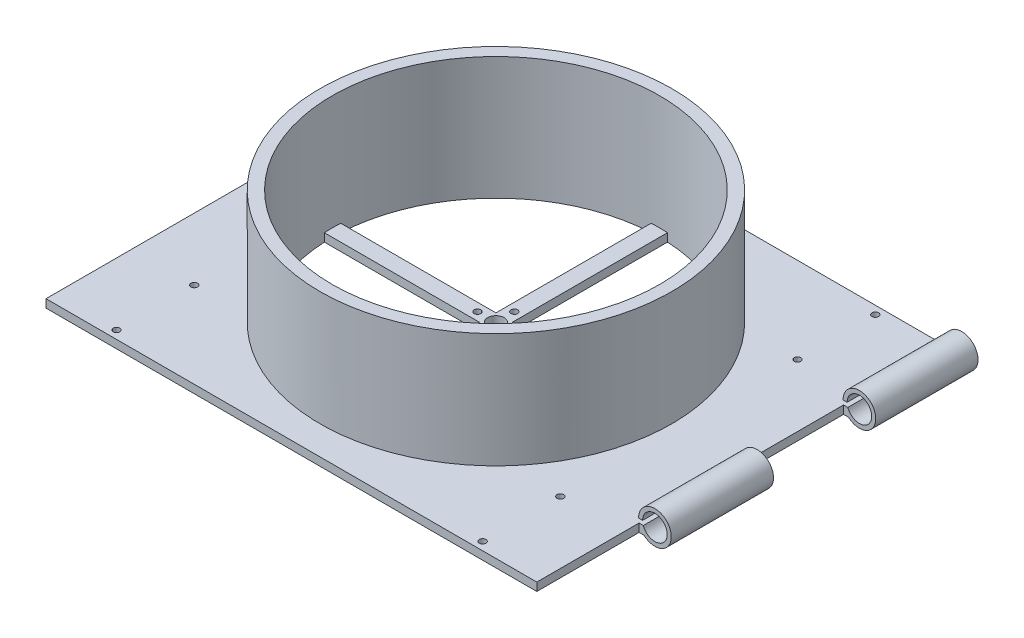
SolidWorks part; units mm, degrees
ref_plane "Alzado" through (0, 0, 0) normal (0, 0, 1) x (1, 0, 0)
ref_plane "Planta" through (0, 0, 0) normal (0, 1, 0) x (1, 0, 0)
ref_plane "Vista lateral" through (0, 0, 0) normal (1, 0, 0) x (0, 0, -1)
sketch "Croquis1" plane through (0, 0, 0) normal (0, 1, 0) x (1, 0, 0)
  circle A0 centre (0, 0) radius 40
  circle A1 centre (0, 0) radius 43
  point P7 (0, 0)
  point P10 (0, 0)
  dimension "D1" = 80
  dimension "D2" = 3
extrude "Saliente-Extruir1" add sketch "Croquis1" along normal blind 30 contours A1 A0
sketch "Croquis3" plane through (0, 0, 0) normal (0, 1, 0) x (1, 0, 0)
  line L1 (0, -40) -> (0, 40) construction
  line L8 (-40, 0) -> (40, 0) construction
  line L13 (-2, 2) -> (-2, 39.95)
  line L18 (-2, -39.95) -> (-2, -2)
  line L20 (2, -39.95) -> (2, -2)
  line L22 (-1.9287, -39.9535) -> (1.9287, 39.9535) construction
  line L23 (-1.9287, 39.9535) -> (1.9287, -39.9535) construction
  line L24 (-39.95, -2) -> (-2, -2)
  line L27 (-39.95, 2) -> (-2, 2)
  line L29 (-39.9548, -1.9002) -> (39.9548, 1.9002) construction
  line L30 (-39.9548, 1.9002) -> (39.9548, -1.9002) construction
  line L31 (2, 2) -> (39.95, 2)
  line L32 (2, 2) -> (2, 39.95)
  line L33 (2, -2) -> (39.95, -2)
  circle A0 centre (0, 0) radius 40 construction
  circle A1 centre (0, 0) radius 40
  circle A2 centre (0, 0) radius 2
  circle A3 centre (4.5, 0) radius 0.81
  circle A9 centre (-4.5, 0) radius 0.81
  circle A11 centre (0, -4.5) radius 0.81
  circle A12 centre (0, 4.5) radius 0.81
  dimension "D3" = 1.62
  dimension "D4" = 4.5
  dimension "D5" = 1.62
  dimension "D1" = 4
  dimension "D2" = 4
  dimension "D6" = 4.5
extrude "Saliente-Extruir2" add sketch "Croquis3" along normal blind 2
sketch "Croquis4" plane through (0, 0, 0) normal (0, 1, 0) x (1, 0, 0)
  line L0 (0, 0) -> (43, 0) construction
  line L5 (-60, -50) -> (60, -50)
  line L6 (-60, -50) -> (-60, 50)
  line L7 (-60, 50) -> (60, 50)
  line L8 (60, -50) -> (60, 50)
  line L9 (-60, -50) -> (60, 50) construction
  line L10 (-60, 50) -> (60, -50) construction
  circle A0 centre (0, 0) radius 43 construction
  circle A1 centre (0, 0) radius 43
  point P0 (0, 0)
  point P1 (0, 0)
  dimension "D1" = 60
  dimension "D3" = 43
  dimension "D2" = 50
  dimension "D4" = 17
extrude "Saliente-Extruir3" add sketch "Croquis4" along normal blind 2
sketch "Croquis5" plane through (0, 2, 0) normal (0, 1, 0) x (1, 0, 0)
  line L0 (-60, -50) -> (60, -50) construction
  line L2 (-44.755, -48) -> (-44.755, -29) construction
  line L3 (0, 0) -> (38.3261, 0) construction
  line L4 (-60, 50) -> (-60, -50) construction
  line L5 (0, 0) -> (0, 15.249) construction
  circle A4 centre (-44.755, -48) radius 0.81
  circle A5 centre (-44.755, -29) radius 0.81
  circle A6 centre (-44.755, 29) radius 0.81
  circle A7 centre (-44.755, 48) radius 0.81
  circle A8 centre (44.755, -48) radius 0.81
  circle A9 centre (44.755, -29) radius 0.81
  circle A10 centre (44.755, 29) radius 0.81
  circle A11 centre (44.755, 48) radius 0.81
  dimension "D1" = 1.62
  dimension "D2" = 19
  dimension "D3" = 15.245
  dimension "D4" = 2
extrude "Cortar-Extruir1" cut sketch "Croquis5" against normal blind 2
ref_plane "Plano1" through (0, 0, -50) normal (0, 0, -1) x (-1, 0, 0)
sketch "Croquis7" plane through (0, 0, -50) normal (0, 0, -1) x (-1, 0, 0)
  line L0 (-60, 0) -> (-58.7728, 0)
  line L1 (60, 0) -> (-60, 0) construction
  line L2 (-59.127, 3) -> (-60.127, 3) construction
  line L3 (-61.0446, 2) -> (-58.9554, 2)
  line L4 (0, 0) -> (0, 6.485) construction
  line L5 (-60, 0) -> (-60, 10.0709) construction
  line L8 (-60.873, 3) -> (-59.873, 3)
  line L9 (-60, 0) -> (-60, 2)
  line L10 (-61.2272, 0) -> (-60, 0)
  line L11 (-61.2272, 0) -> (-60, 0)
  arc A1 (-58.7728, 0) -> (-60.127, 3) centre (-56.127, 3) ccw construction
  arc A3 (-58.9554, 2) -> (-59.127, 3) centre (-56.127, 3) ccw construction
  arc A4 (-61.0446, 2) -> (-60.873, 3) centre (-63.873, 3) cw
  arc A5 (-61.2272, 0) -> (-59.873, 3) centre (-63.873, 3) cw
  point P13 (-60, 2)
  dimension "D1" = 8
  dimension "D2" = 6
  dimension "D3" = 3
extrude "Saliente-Extruir8" add sketch "Croquis7" against normal blind 25 contours A5 L10 L9 L3 A4 L8
pattern_linear "MatrizL2" count 2 spacing 50 along (0, 0, 1) of "Saliente-Extruir8"
